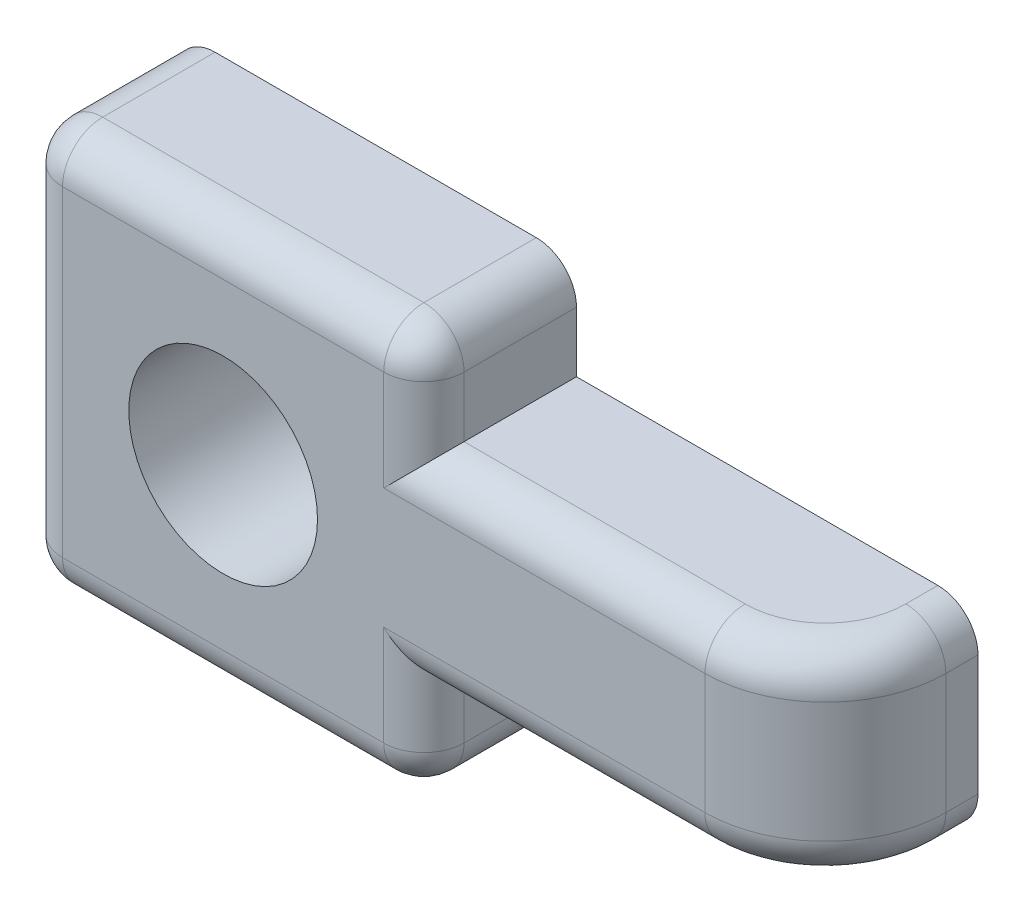
SolidWorks part; units mm, degrees
ref_plane "前视基准面" through (0, 0, 0) normal (0, 0, 1) x (1, 0, 0)
ref_plane "上视基准面" through (0, 0, 0) normal (0, 1, 0) x (1, 0, 0)
ref_plane "右视基准面" through (0, 0, 0) normal (1, 0, 0) x (0, 0, -1)
sketch "草图1" plane through (0, 0, 0) normal (0, 0, 1) x (1, 0, 0)
  line L0 (0, 0) -> (0, 48.2102) construction
  line L1 (50, -50) -> (50, 50)
  line L2 (50, 0) -> (-50, 0)
  line L3 (0, 0) -> (0, 50)
  line L4 (50, 50) -> (-50, 50)
  line L5 (-50, -50) -> (-50, 50)
  line L6 (50, -50) -> (-50, -50)
  line L7 (0, -25) -> (150, -25)
  line L8 (0, 0) -> (150, 0)
  line L9 (0, -25) -> (0, 25)
  line L10 (0, 25) -> (150, 25)
  line L11 (150, -25) -> (150, 25)
  circle A0 centre (0, 0) radius 23.5
  dimension "D1" = 47
  dimension "D2" = 50
  dimension "D3" = 50
  dimension "D4" = 25
  dimension "D5" = 150
extrude "凸台-拉伸1" add sketch "草图1" along normal blind 38 contours A0 L9 L3 L4 L5 L2 | L6 L0 L9 A0 L2 L5 | L0 L6 L1 L7 | A0 L9 L7 L1 L2 | A0 L2 L1 L10 L9 | L3 L10 L1 L4 | L8 L11 L10 L1 | L7 L11 L8 L1
fillet "圆角1" radius 10 4 edges at (50, 50, 19) (50, -50, 19) (-50, -50, 19) (-50, 50, 19)
fillet "圆角2" radius 30 1 edges at (150, 0, 38)
fillet "圆角3" radius 10 15 edges at (50, -32.5, 38) (47.0711, -47.0711, 38) (0, -50, 38) (-47.0711, -47.0711, 38) (-50, 0, 38) (-47.0711, 47.0711, 38) (0, 50, 38) (47.0711, 47.0711, 38) (150, -25, 4) (141.2132, -25, 29.2132) (150, 25, 4) (141.2132, 25, 29.2132) (50, 32.5, 38) (85, -25, 38) (85, 25, 38)
